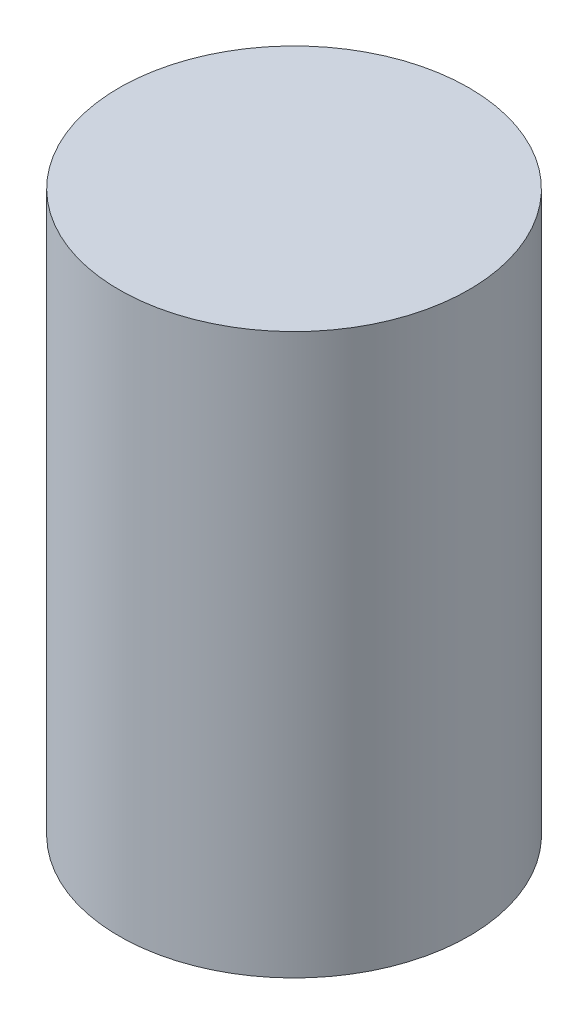
SolidWorks part; units mm, degrees
material "Plastique personnalisé"
ref_plane "Plan de face" through (0, 0, 0) normal (0, 0, 1) x (1, 0, 0)
ref_plane "Plan de dessus" through (0, 0, 0) normal (0, 1, 0) x (1, 0, 0)
ref_plane "Plan de droite" through (0, 0, 0) normal (1, 0, 0) x (0, 0, -1)
sketch "Esquisse1" plane through (0, 0, 0) normal (0, 0, 1) x (1, 0, 0)
  line L0 (0, -6.9457) -> (0, -11.5761)
  line L2 (-12.5, -7.9457) -> (12.5, -7.9457)
  line L3 (-12.5, -7.9457) -> (-12.5, -6.9457)
  line L5 (12.5, -7.9457) -> (12.5, -6.9457)
  line L6 (-12.5, -7.9457) -> (12.5, -6.9457) construction
  line L7 (0, -7.4457) -> (12.5, -7.9457) construction
  line L11 (0, 12.0543) -> (0, -27.0147)
  line L12 (0, -27.0147) -> (0, 44.1726)
  line L15 (12.5, 32.0543) -> (12.5, 31.0543)
  line L17 (-12.5, 32.0543) -> (12.5, 32.0543)
  line L18 (-12.5, 32.0543) -> (-12.5, 31.0543)
  line L20 (-12.5, 31.0543) -> (-12.5, -6.9457)
  line L22 (12.5, -6.9457) -> (12.5, 31.0543)
  point P3 (0, -7.4457)
  point P9 (0, 12.0543)
  dimension "D1" = 1
  dimension "D2" = 25
revolve "Révolution1" add sketch "Esquisse1" angle 360 about L12
